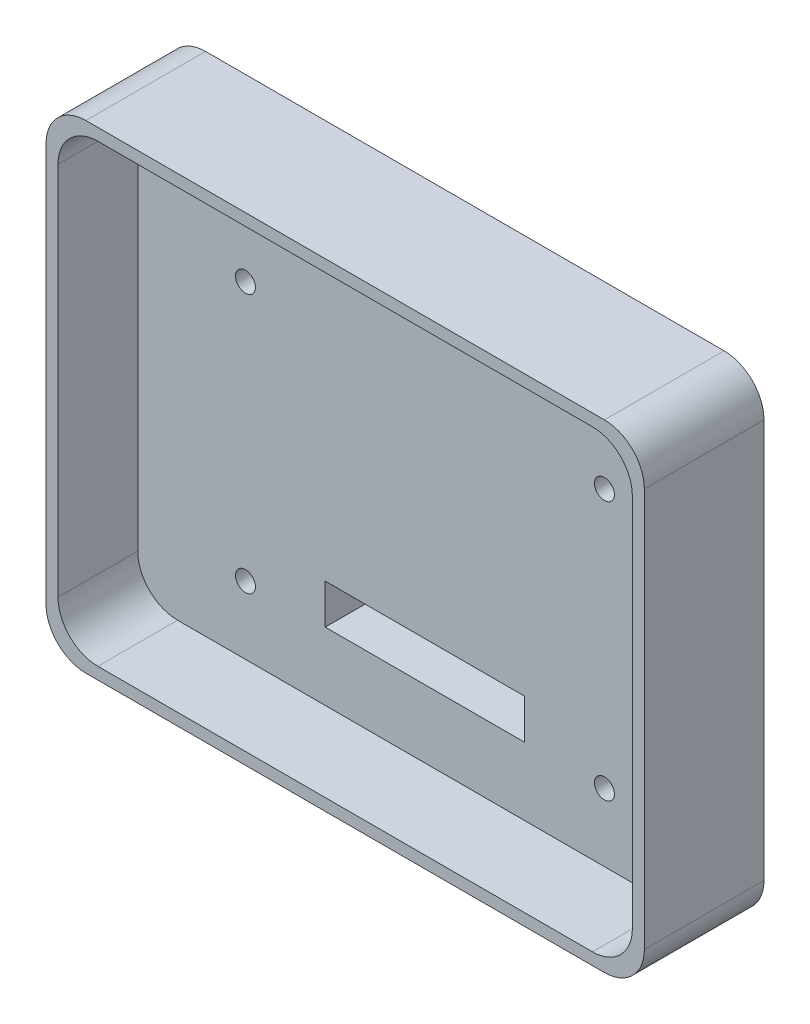
SolidWorks part; units mm, degrees
ref_plane "Front Plane" through (0, 0, 0) normal (0, 0, 1) x (1, 0, 0)
ref_plane "Top Plane" through (0, 0, 0) normal (0, 1, 0) x (1, 0, 0)
ref_plane "Right Plane" through (0, 0, 0) normal (1, 0, 0) x (0, 0, -1)
sketch "Sketch1" plane through (0, 0, 0) normal (0, 0, 1) x (1, 0, 0)
  line L1 (-324.6687, 84.7962) -> (-174.6687, 84.7962)
  line L2 (-324.6687, 84.7962) -> (-324.6687, -35.2038)
  line L3 (-324.6687, -35.2038) -> (-174.6687, -35.2038)
  line L4 (-174.6687, 84.7962) -> (-174.6687, -35.2038)
  line L5 (-324.6687, 84.7962) -> (-174.6687, -35.2038) construction
  line L6 (-324.6687, -35.2038) -> (-174.6687, 84.7962) construction
  point P0 (-249.6687, 24.7962)
  dimension "D1" = 150
  dimension "D2" = 120
extrude "Boss-Extrude1" add sketch "Sketch1" along normal blind 30
sketch "Sketch2" plane through (0, 0, 0) normal (0, 0, -1) x (-1, 0, 0)
  line L1 (249.6687, -35.2038) -> (249.6687, 84.7962) construction
  line L3 (174.6687, 84.7962) -> (324.6687, 84.7962) construction
  line L4 (324.6687, -35.2038) -> (174.6687, -35.2038) construction
  line L5 (192.1687, -35.2038) -> (217.1687, -35.2038)
  line L6 (192.1687, -35.2038) -> (192.1687, 69.7962)
  line L7 (192.1687, 69.7962) -> (217.1687, 69.7962)
  line L8 (217.1687, -35.2038) -> (217.1687, 69.7962)
  line L10 (282.1687, -35.2038) -> (307.1687, -35.2038)
  line L11 (282.1687, -35.2038) -> (282.1687, 69.7962)
  line L18 (282.1687, 69.7962) -> (307.1687, 69.7962)
  line L19 (307.1687, -35.2038) -> (307.1687, 69.7962)
  dimension "D1" = 105
  dimension "D2" = 105
  dimension "D3" = 32.5
  dimension "D4" = 25
  dimension "D5" = 32.5
  dimension "D6" = 25
extrude "Cut-Extrude1" cut sketch "Sketch2" against normal blind 6.5
sketch "Sketch4" plane through (0, 0, 30) normal (0, 0, 1) x (1, 0, 0)
  line L0 (-174.6687, 84.7962) -> (-324.6687, 84.7962) construction
  line L1 (-321.6687, 81.7962) -> (-177.6687, 81.7962)
  line L2 (-321.6687, 81.7962) -> (-321.6687, -32.2038)
  line L3 (-321.6687, -32.2038) -> (-177.6687, -32.2038)
  line L4 (-177.6687, 81.7962) -> (-177.6687, -32.2038)
  line L5 (-321.6687, 81.7962) -> (-177.6687, -32.2038) construction
  line L6 (-321.6687, -32.2038) -> (-177.6687, 81.7962) construction
  line L7 (-324.6687, 84.7962) -> (-324.6687, -35.2038) construction
  line L8 (-324.6687, -35.2038) -> (-174.6687, -35.2038) construction
  line L9 (-174.6687, -35.2038) -> (-174.6687, 84.7962) construction
  point P0 (-249.6687, 24.7962)
  dimension "D1" = 3
  dimension "D2" = 3
  dimension "D3" = 3
  dimension "D4" = 3
extrude "Cut-Extrude2" cut sketch "Sketch4" against normal blind 20
fillet "Fillet1" radius 10 8 edges at (-324.6687, -35.2038, 15) (-174.6687, -35.2038, 15) (-174.6687, 84.7962, 15) (-324.6687, 84.7962, 15) (-177.6687, -32.2038, 20) (-321.6687, -32.2038, 20) (-321.6687, 81.7962, 20) (-177.6687, 81.7962, 20)
hole_wizard "Ø5.0mm Dowel Hole1" positions "Sketch10" profile "Sketch11" hole size "Ø5.0" standard "ISO"
sketch "Sketch10" plane through (0, 0, 6.5) normal (0, 0, -1) x (-1, 0, 0)
  line L0 (192.1687, 69.7962) -> (192.1687, -35.2038) construction
  line L1 (217.1687, 69.7962) -> (192.1687, 69.7962) construction
  line L2 (192.1687, -35.2038) -> (217.1687, -35.2038) construction
  line L3 (307.1687, -35.2038) -> (307.1687, 69.7962) construction
  line L4 (307.1687, -35.2038) -> (307.1687, 69.7962) construction
  line L5 (282.1687, -35.2038) -> (307.1687, -35.2038) construction
  line L6 (307.1687, 69.7962) -> (282.1687, 69.7962) construction
  point P0 (204.6687, 49.7962)
  point P2 (204.6687, -15.2038)
  point P4 (294.6687, 49.7962)
  point P6 (294.6687, -15.2038)
  dimension "D1" = 12.5
  dimension "D2" = 20
  dimension "D3" = 20
  dimension "D4" = 12.5
  dimension "D5" = 12.5
  dimension "D6" = 12.5
  dimension "D7" = 20
  dimension "D8" = 20
sketch "Sketch11" plane through (-204.6687, 49.7962, 6.5) normal (1, 0, 0) x (0, 1, 0)
  line L0 (0, 0) -> (0, 21.5022)
  line L1 (0, 21.5022) -> (2.5, 20)
  line L2 (2.5, 20) -> (2.5, 0)
  line L5 (2.5, 0) -> (0, 0)
  line L10 (0, 21.5022) -> (-2.5, 20) construction
  line L11 (0, -6.35) -> (0, 107.95) construction
  dimension "Hole Dia." = 5
  dimension "Hole Depth" = 20
  dimension "Drill Angle" = 118
sketch "Sketch12" plane through (0, 0, 0) normal (0, 0, -1) x (-1, 0, 0)
  line L0 (249.6687, -35.2038) -> (249.6687, -10.2038) construction
  line L1 (224.6687, -5.2038) -> (274.6687, -5.2038)
  line L2 (224.6687, -5.2038) -> (224.6687, -15.2038)
  line L3 (224.6687, -15.2038) -> (274.6687, -15.2038)
  line L4 (274.6687, -5.2038) -> (274.6687, -15.2038)
  line L5 (224.6687, -5.2038) -> (274.6687, -15.2038) construction
  line L6 (224.6687, -15.2038) -> (274.6687, -5.2038) construction
  line L7 (282.1687, -35.2038) -> (217.1687, -35.2038) construction
  point P0 (249.6687, -10.2038)
  dimension "D1" = 50
  dimension "D2" = 10
  dimension "D3" = 20
extrude "Cut-Extrude6" cut sketch "Sketch12" against normal through all
